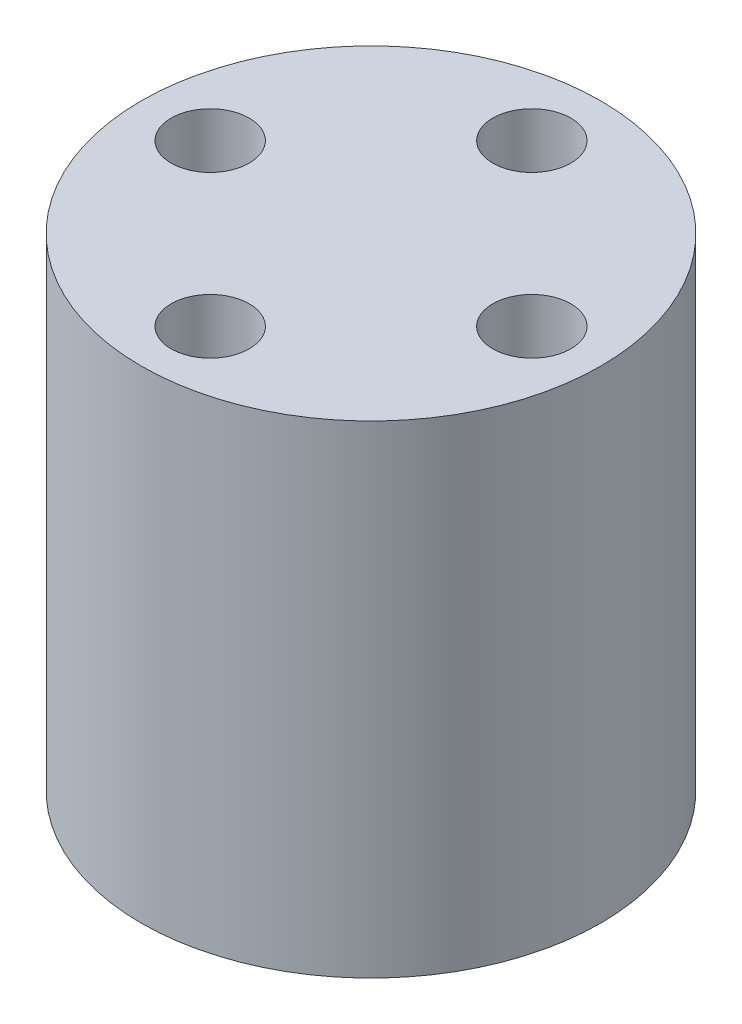
SolidWorks part; units mm, degrees
ref_plane "前视基准面" through (0, 0, 0) normal (0, 0, 1) x (1, 0, 0)
ref_plane "上视基准面" through (0, 0, 0) normal (0, 1, 0) x (1, 0, 0)
ref_plane "右视基准面" through (0, 0, 0) normal (1, 0, 0) x (0, 0, -1)
sketch "草图1" plane through (0, 0, 0) normal (0, 1, 0) x (1, 0, 0)
  circle A0 centre (0, 0) radius 10
  circle A1 centre (0, 0) radius 7 construction
  circle A2 centre (0, 7) radius 1.7
  circle A3 centre (7, 0) radius 1.7
  circle A4 centre (0, -7) radius 1.7
  circle A5 centre (-7, 0) radius 1.7
  point P14 (0, 0)
  dimension "D1" = 20
  dimension "D2" = 14
  dimension "D3" = 3.4
  dimension "D4" = 4
extrude "凸台-拉伸1" add sketch "草图1" along normal blind 21
